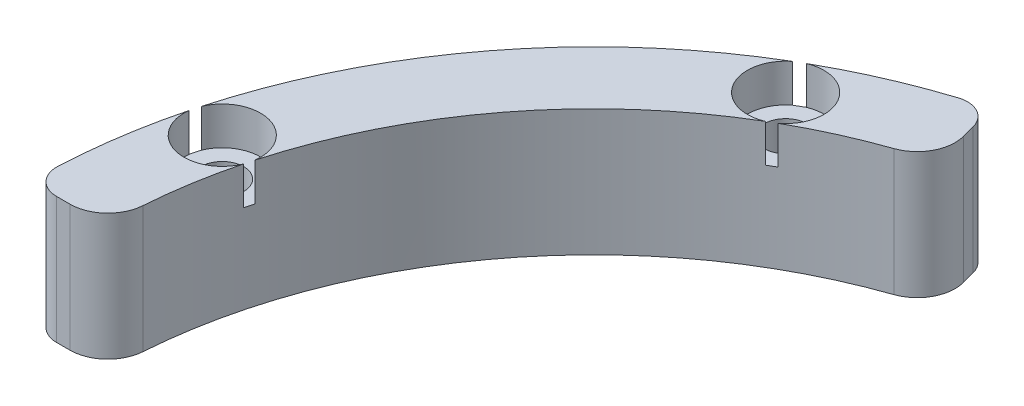
SolidWorks part; units mm, degrees
ref_plane "Спереди" through (0, 0, 0) normal (0, 0, 1) x (1, 0, 0)
ref_plane "Сверху" through (0, 0, 0) normal (0, 1, 0) x (1, 0, 0)
ref_plane "Справа" through (0, 0, 0) normal (1, 0, 0) x (0, 0, -1)
ref_plane "Плоскость4" through (0, 0, 0) normal (0.9659, 0, -0.2588) x (0, 1, 0)
sketch "Эскиз1" plane through (0, 0, 0) normal (0.9659, 0, -0.2588) x (0, 1, 0)
  line L0 (10, -44.5) -> (10, -38.5)
  line L1 (10, -38.5) -> (0, -38.5)
  line L2 (0, -38.5) -> (0, -44.5)
  line L3 (0, -44.5) -> (10, -44.5)
  line L4 (10, 0) -> (0, 0) construction
revolve "Повернуть1" add sketch "Эскиз1" angle 75 about L4
hole_wizard "Цековка для винта с заклепочной головкой M31" positions "Эскиз3" profile "Эскиз2" counterbore size "M3" standard "Ansi Metric"
sketch "Эскиз3" plane through (0, 10, 0) normal (0, 1, 0) x (1, 0, 0)
  point P0 (-40.0859, 10.741)
  point P1 (-20.75, 35.9401)
sketch "Эскиз2" plane through (-40.0859, 10, -10.741) normal (1, 0, 0) x (0, 0, 1)
  line L0 (0, 0) -> (0, 10)
  line L1 (0, 10) -> (1.7, 10)
  line L3 (1.7, 10) -> (1.7, 3)
  line L4 (1.7, 3) -> (3.025, 3)
  line L5 (3.025, 3) -> (3.025, 0)
  line L7 (3.025, 0) -> (0, 0)
  line L11 (0, -6.35) -> (0, 107.95) construction
  dimension "Диаметр сквозного отверстия" = 3.4
  dimension "Глубина сквозного отверстия" = 10
  dimension "Диаметр цековки" = 6.05
  dimension "Глубина цековки" = 3
fillet "Скругление1" radius 2 2 edges at (-11.5174, 5, -42.9837) (-44.5, 5, 0)
fillet "Скругление2" radius 3 2 edges at (-38.5, 5, 0) (-9.9645, 5, -37.1881)
